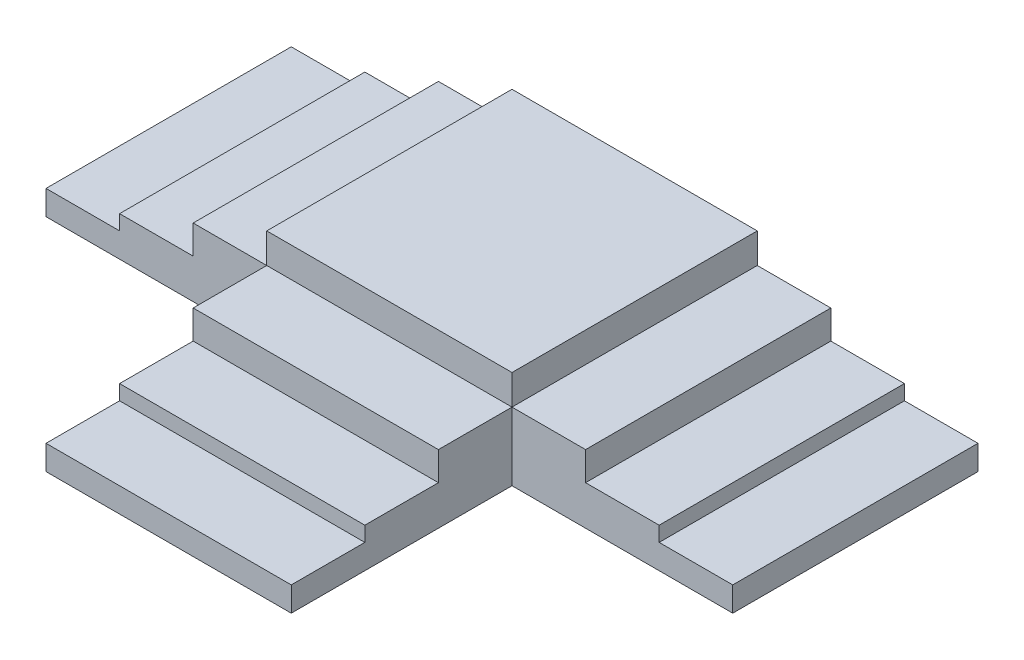
SolidWorks part; units mm, degrees
ref_plane "前视基准面" through (0, 0, 0) normal (0, 0, 1) x (1, 0, 0)
ref_plane "上视基准面" through (0, 0, 0) normal (0, 1, 0) x (1, 0, 0)
ref_plane "右视基准面" through (0, 0, 0) normal (1, 0, 0) x (0, 0, -1)
sketch "草图1" plane through (0, 0, 0) normal (0, 1, 0) x (1, 0, 0)
  line L1 (-500, 500) -> (500, 500)
  line L2 (-500, 500) -> (-500, -500)
  line L3 (-500, -500) -> (500, -500)
  line L4 (500, 500) -> (500, -500)
  line L5 (-500, 500) -> (500, -500) construction
  line L6 (-500, -500) -> (500, 500) construction
  point P0 (0, 0)
  dimension "D1" = 1000
  dimension "D2" = 1000
extrude "凸台-拉伸1" add sketch "草图1" along normal blind 400
sketch "草图2" plane through (0, 0, -500) normal (0, 0, -1) x (-1, 0, 0)
  line L0 (500, 0) -> (1400, 0)
  line L1 (1400, 0) -> (1400, 100)
  line L2 (1400, 100) -> (1100, 100)
  line L3 (1100, 100) -> (1100, 160.855)
  line L4 (1100, 160.855) -> (800, 160.855)
  line L5 (800, 160.855) -> (800, 277.7538)
  line L6 (800, 277.7538) -> (500, 277.7538)
  line L7 (500, 400) -> (500, 0) construction
  line L8 (500, 277.7538) -> (500, 0)
  point P4 (-0.0885, 291.8416)
  point P13 (3.0778, 259.1239)
  dimension "D1" = 900
  dimension "D2" = 100
  dimension "D3" = 160.855
  dimension "D4" = 277.7538
  dimension "D5" = 300
  dimension "D6" = 300
  dimension "D7" = 300
extrude "凸台-拉伸2" add sketch "草图2" against normal up to surface (1000 mm away) up to face at (0, 200, 500)
sketch "草图4" plane through (-500, 0, 0) normal (-1, 0, 0) x (0, 0, 1)
  line L0 (500, 0) -> (1400, 0)
  line L1 (1400, 0) -> (1400, 100)
  line L2 (1400, 100) -> (1100, 100)
  line L3 (1100, 100) -> (1100, 160.855)
  line L4 (1100, 160.855) -> (800, 160.855)
  line L5 (800, 160.855) -> (800, 277.7538)
  line L6 (800, 277.7538) -> (500, 277.7538)
  line L7 (500, 277.7538) -> (500, 0)
  line L8 (500, 0) -> (-500, 0) construction
  line L9 (500, 400) -> (500, 277.7538) construction
  dimension "D1" = 900
  dimension "D2" = 100
  dimension "D3" = 160.855
  dimension "D4" = 277.7538
  dimension "D5" = 300
  dimension "D6" = 300
  dimension "D7" = 300
extrude "凸台-拉伸3" add sketch "草图4" against normal up to surface (1000 mm away) up to face at (500, 200, 0)
sketch "草图5" plane through (0, 0, 500) normal (0, 0, 1) x (1, 0, 0)
  line L0 (500, 0) -> (1400, 0)
  line L1 (1400, 0) -> (1400, 100)
  line L2 (1400, 100) -> (1100, 100)
  line L3 (1100, 100) -> (1100, 160.855)
  line L4 (1100, 160.855) -> (800, 160.855)
  line L5 (800, 160.855) -> (800, 277.7538)
  line L6 (800, 277.7538) -> (500, 277.7538)
  line L7 (500, 277.7538) -> (500, 0)
  line L8 (500, 0) -> (-500, 0) construction
  line L9 (500, 400) -> (500, 277.7538) construction
  dimension "D1" = 900
  dimension "D2" = 100
  dimension "D3" = 160.855
  dimension "D4" = 277.7538
  dimension "D5" = 300
  dimension "D6" = 300
  dimension "D7" = 300
extrude "凸台-拉伸4" add sketch "草图5" against normal up to surface (1000 mm away) up to face at (-660, 187.7218, -500)
